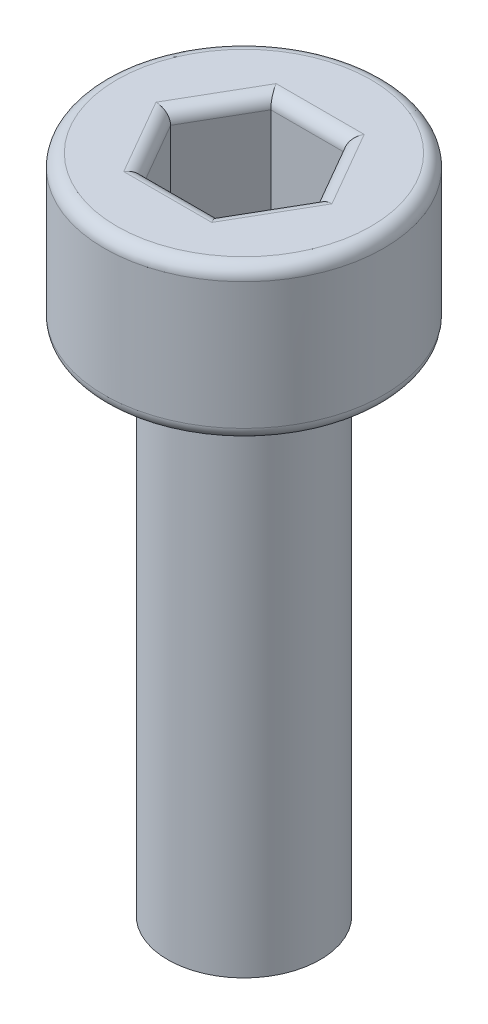
SolidWorks part; units mm, degrees
ref_plane "Front Plane" through (0, 0, 0) normal (0, 0, 1) x (1, 0, 0)
ref_plane "Top Plane" through (0, 0, 0) normal (0, 1, 0) x (1, 0, 0)
ref_plane "Right Plane" through (0, 0, 0) normal (1, 0, 0) x (0, 0, -1)
sketch "Sketch1" plane through (0, 0, 0) normal (0, 0, 1) x (1, 0, 0)
  line L0 (0, 21.3223) -> (0, -43.638) construction
sketch "Sketch2" plane through (0, 0, 0) normal (0, 0, 1) x (1, 0, 0)
  line L0 (0, 3) -> (2.75, 3)
  line L1 (0, 200021.3223) -> (0, -200043.638) construction
  line L2 (2.75, 3) -> (2.75, 0)
  line L3 (2.75, 0) -> (1.5, 0)
  line L4 (1.5, 0) -> (1.5, -10)
  line L5 (1.5, -10) -> (0, -10)
  line L6 (0, -10) -> (0, 3)
  dimension "D1" = 1.5
  dimension "D2" = 2.75
  dimension "D3" = 3
  dimension "D4" = 10
revolve "Revolve1" add sketch "Sketch2" angle 360 about L0
sketch "Sketch3" plane through (0, 3, 0) normal (0, 1, 0) x (1, 0, 0)
  line L0 (0, 0) -> (1.4434, 0) construction
  line L1 (1.4434, 0) -> (0.7217, 1.25)
  line L2 (0.7217, 1.25) -> (-0.7217, 1.25)
  line L3 (-0.7217, 1.25) -> (-1.4434, 0)
  line L4 (-1.4434, 0) -> (-0.7217, -1.25)
  line L5 (-0.7217, -1.25) -> (0.7217, -1.25)
  line L6 (0.7217, -1.25) -> (1.4434, 0)
  circle A0 centre (0, 0) radius 1.25 construction
  dimension "D1" = 2.5
extrude "Cut-Extrude1" cut sketch "Sketch3" against normal blind 2
fillet "Fillet1" radius 0.25 9 edges at (-1.5, 0, 0) (-2.75, 0, 0) (-2.75, 3, 0) (0, 3, -1.25) (-1.0825, 3, -0.625) (-1.0825, 3, 0.625) (0, 3, 1.25) (1.0825, 3, 0.625) (1.0825, 3, -0.625)
